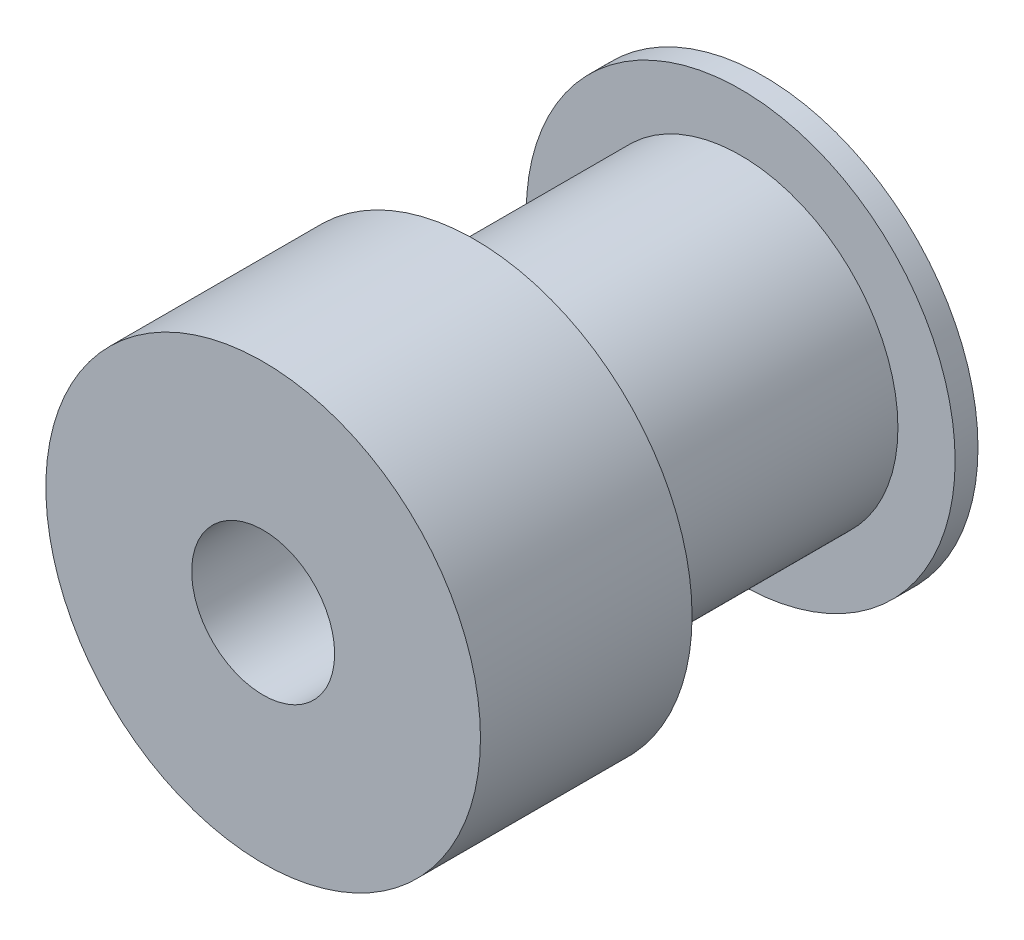
SolidWorks part; units mm, degrees
ref_plane "Спереди" through (0, 0, 0) normal (0, 0, 1) x (1, 0, 0)
ref_plane "Сверху" through (0, 0, 0) normal (0, 1, 0) x (1, 0, 0)
ref_plane "Справа" through (0, 0, 0) normal (1, 0, 0) x (0, 0, -1)
sketch "Эскиз1" plane through (0, 0, 0) normal (0, 0, 1) x (1, 0, 0)
  circle A0 centre (0, 0) radius 7.5
  dimension "D1" = 15
extrude "Бобышка-Вытянуть1" add sketch "Эскиз1" along normal blind 0.8
sketch "Эскиз2" plane through (0, 0, 0.8) normal (0, 0, 1) x (1, 0, 0)
  circle A0 centre (0, 0) radius 5.5
  dimension "D1" = 11
extrude "Бобышка-Вытянуть2" add sketch "Эскиз2" along normal blind 9.3
sketch "Эскиз3" plane through (0, 0, 10.1) normal (0, 0, 1) x (1, 0, 0)
  circle A0 centre (0, 0) radius 7.6
  dimension "D1" = 15.2
extrude "Бобышка-Вытянуть3" add sketch "Эскиз3" along normal blind 7.4
sketch "Эскиз4" plane through (0, 0, 17.5) normal (0, 0, 1) x (1, 0, 0)
  circle A0 centre (0, 0) radius 2.5
  dimension "D1" = 5
extrude "Вырез-Вытянуть1" cut sketch "Эскиз4" against normal through all
